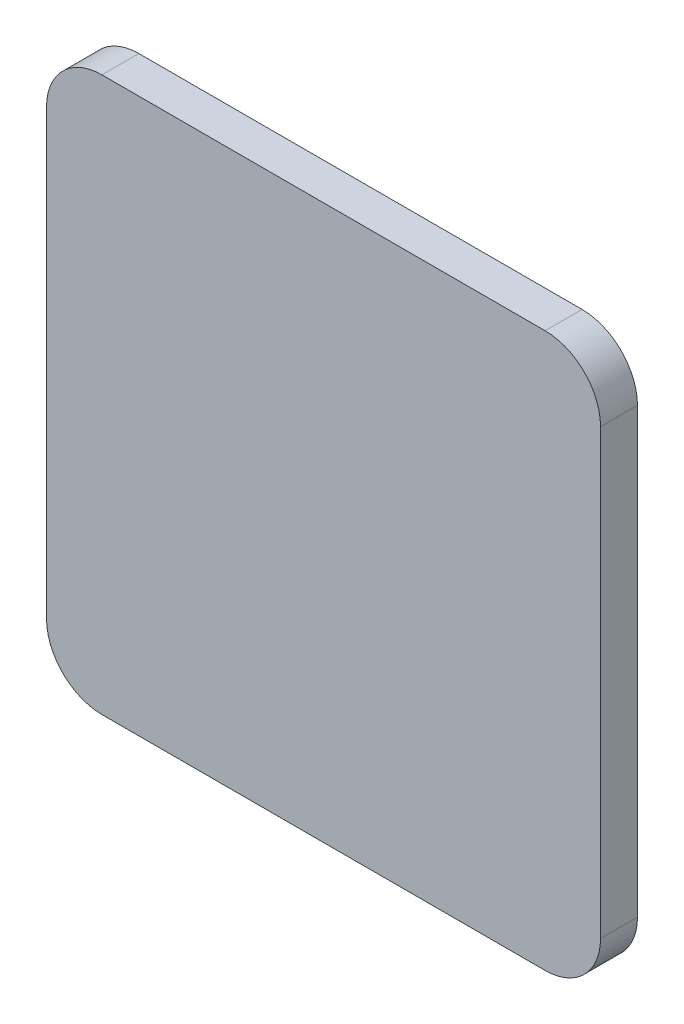
SolidWorks part; units mm, degrees
ref_plane "Ön Düzlem" through (0, 0, 0) normal (0, 0, 1) x (1, 0, 0)
ref_plane "Üst Düzlem" through (0, 0, 0) normal (0, 1, 0) x (1, 0, 0)
ref_plane "Sağ Düzlem" through (0, 0, 0) normal (1, 0, 0) x (0, 0, -1)
sketch "Çizim1" plane through (0, 0, 0) normal (0, 0, 1) x (1, 0, 0)
  line L1 (75, -75) -> (-75, -75)
  line L2 (75, -75) -> (75, 75)
  line L3 (75, 75) -> (-75, 75)
  line L4 (-75, -75) -> (-75, 75)
  line L5 (75, -75) -> (-75, 75) construction
  line L6 (75, 75) -> (-75, -75) construction
  point P0 (0, 0)
  dimension "D1" = 150
  dimension "D2" = 150
extrude "Yükseklik-Ekstrüzyon1" add sketch "Çizim1" along normal blind 10
fillet "Radyus1" radius 15 4 edges at (-75, 75, 5) (-75, -75, 5) (75, -75, 5) (75, 75, 5)
